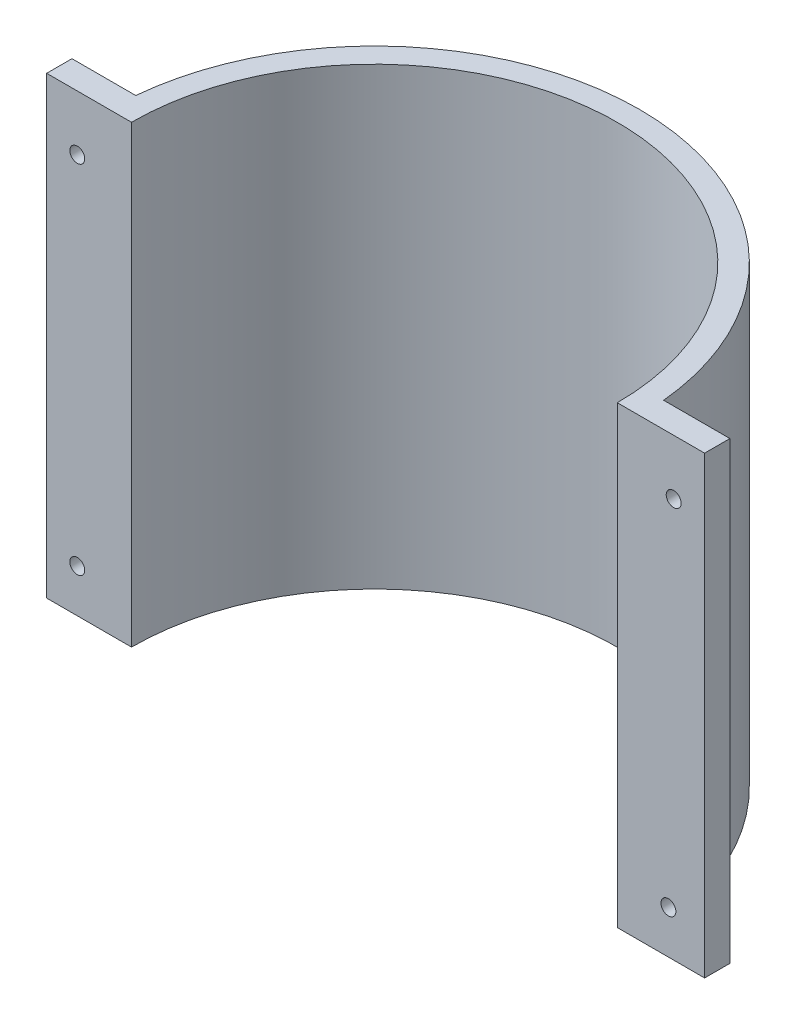
SolidWorks part; units mm, degrees
ref_plane "Front Plane" through (0, 0, 0) normal (0, 0, 1) x (1, 0, 0)
ref_plane "Top Plane" through (0, 0, 0) normal (0, 1, 0) x (1, 0, 0)
ref_plane "Right Plane" through (0, 0, 0) normal (1, 0, 0) x (0, 0, -1)
sketch "Sketch1" plane through (0, 0, 0) normal (0, 1, 0) x (1, 0, 0)
  line L0 (-44.45, 0) -> (44.45, 0)
  line L2 (-40.7168, 0) -> (-54.9362, 0)
  line L3 (-40.7168, 0) -> (-40.7168, 4.2412)
  line L4 (-40.7168, 4.2412) -> (-54.9362, 4.2412)
  line L5 (-54.9362, 0) -> (-54.9362, 4.2412)
  line L6 (40.7168, 0) -> (55.3596, 0)
  line L7 (40.7168, 0) -> (40.7168, 4.2412)
  line L8 (40.7168, 4.2412) -> (55.3596, 4.2412)
  line L9 (55.3596, 0) -> (55.3596, 4.2412)
  circle A0 centre (0, 0) radius 44.45
  circle A1 centre (0, 0) radius 40.7168
extrude "Boss-Extrude1" add sketch "Sketch1" along normal blind 76.2 contours A1 L7 L8 A0 L4 L3 | L4 A0 L0 L3 | A0 L4 L5 L2 | L0 A0 L8 L7
sketch "Sketch2" plane through (0, 0, -4.2412) normal (0, 0, -1) x (-1, 0, 0)
  circle A0 centre (-49.2914, 7.2315) radius 1.5
  circle A1 centre (-50.1719, 66.9454) radius 1.5
  circle A2 centre (49.8049, 66.9454) radius 1.5
  circle A3 centre (49.8049, 7.2315) radius 1.5
hole_wizard "Tap Drill for M3x0.5 Tap1" positions "3DSketch1" profile "Sketch3" hole size "M3x0.5" standard "ANSI Metric" end condition through all
sketch3d "3DSketch1"
  point P0 (50.1719, 66.9454, -4.2412)
  point P3 (49.2914, 7.2315, -4.2412)
  point P6 (-49.8049, 7.2315, -4.2412)
  point P9 (-49.8049, 66.9454, -4.2412)
sketch "Sketch3" plane through (50.1719, 66.9454, -4.2412) normal (1, 0, 0) x (0, 1, 0)
  line L0 (0, 0) -> (0, 4.2412)
  line L1 (0, 4.2412) -> (1.25, 4.2412)
  line L2 (1.25, 4.2412) -> (1.25, 0.025)
  line L3 (1.25, 0.025) -> (1.275, 0)
  line L5 (1.275, 0) -> (0, 0)
  line L6 (-1.25, 0.025) -> (-1.275, 0) construction
  line L11 (0, -6.35) -> (0, 107.95) construction
  dimension "Thru Hole Dia." = 2.5
  dimension "Thru Hole Depth" = 4.2412
  dimension "Near C'Sink Dia." = 2.55
  dimension "Near C'Sink Angle" = 90
